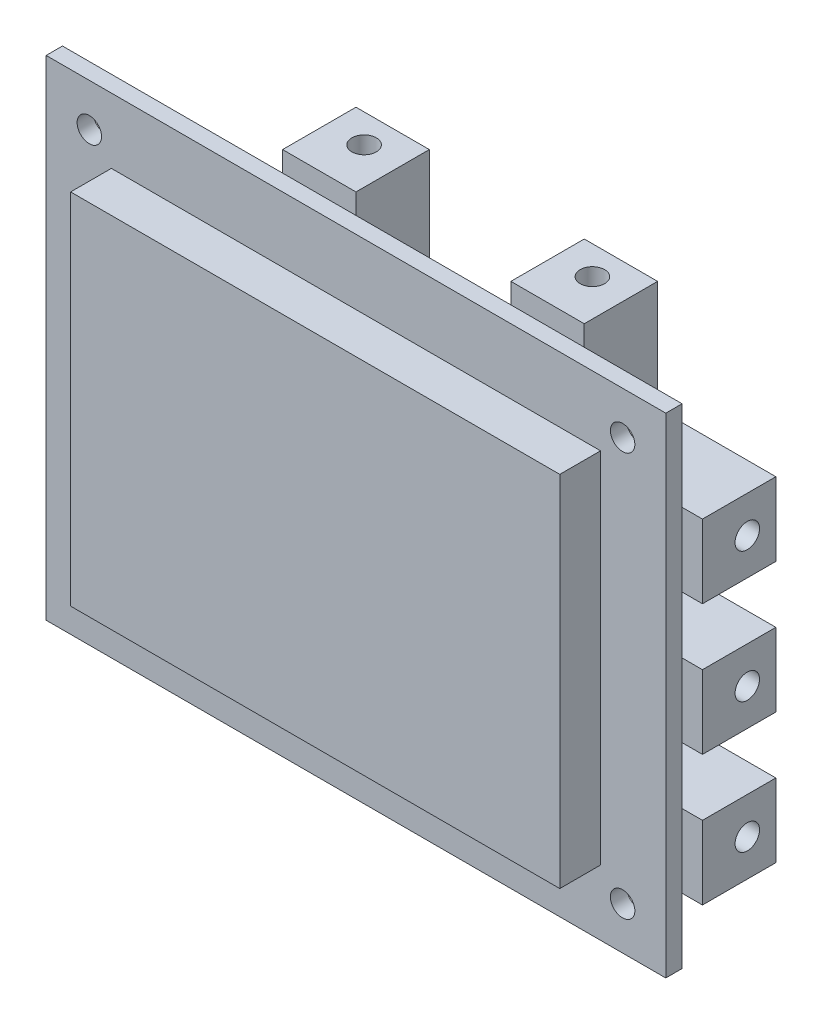
SolidWorks part; units mm, degrees
ref_plane "前视基准面" through (0, 0, 0) normal (0, 0, 1) x (1, 0, 0)
ref_plane "上视基准面" through (0, 0, 0) normal (0, 1, 0) x (1, 0, 0)
ref_plane "右视基准面" through (0, 0, 0) normal (1, 0, 0) x (0, 0, -1)
sketch "草图1" plane through (0, 0, 0) normal (0, 0, 1) x (1, 0, 0)
  line L1 (-38, -30) -> (38, -30)
  line L2 (-38, -30) -> (-38, 30)
  line L3 (-38, 30) -> (38, 30)
  line L4 (38, -30) -> (38, 30)
  line L5 (-38, -30) -> (38, 30) construction
  line L6 (-38, 30) -> (38, -30) construction
  circle A0 centre (-32.705, 24.765) radius 1.5
  circle A1 centre (32.705, 24.765) radius 1.5
  circle A2 centre (-32.705, -24.765) radius 1.5
  circle A3 centre (32.705, -24.765) radius 1.5
  point P0 (0, 0)
  dimension "D4" = 32.705
  dimension "D5" = 3
  dimension "D6" = 49.53
  dimension "D7" = 24.765
  dimension "D1" = 76
  dimension "D2" = 60
  dimension "D3" = 65.41
extrude "凸台-拉伸1" add sketch "草图1" along normal blind 2
sketch "草图2" plane through (0, 0, 2) normal (0, 0, 1) x (1, 0, 0)
  line L0 (38, 30) -> (-38, 30) construction
  line L1 (-30, -22) -> (30, -22)
  line L2 (-30, -22) -> (-30, 22)
  line L3 (-30, 22) -> (30, 22)
  line L4 (30, -22) -> (30, 22)
  line L5 (-30, -22) -> (30, 22) construction
  line L6 (-30, 22) -> (30, -22) construction
  line L7 (38, -30) -> (38, 30) construction
  point P0 (0, 0)
  dimension "D1" = 8
  dimension "D2" = 8
extrude "凸台-拉伸2" add sketch "草图2" along normal blind 5
sketch "草图3" plane through (0, 0, 0) normal (0, 0, -1) x (-1, 0, 0)
  line L0 (38, -30) -> (-38, -30) construction
  line L1 (-40.5, -13) -> (-28.5, -13)
  line L2 (-40.5, -13) -> (-40.5, -22)
  line L3 (-40.5, -22) -> (-28.5, -22)
  line L4 (-28.5, -13) -> (-28.5, -22)
  line L13 (-38, -30) -> (-38, 30) construction
  line L14 (-40.5, 3) -> (-40.5, -6)
  line L15 (-40.5, 3) -> (-28.5, 3)
  line L16 (-28.5, 3) -> (-28.5, -6)
  line L17 (-40.5, -6) -> (-28.5, -6)
  line L18 (-40.5, 19) -> (-40.5, 10)
  line L19 (-40.5, 19) -> (-28.5, 19)
  line L20 (-28.5, 19) -> (-28.5, 10)
  line L21 (-40.5, 10) -> (-28.5, 10)
  line L22 (-38, 30) -> (38, 30) construction
  line L23 (-26, 20.5) -> (-17, 20.5)
  line L24 (-26, 20.5) -> (-26, 32.5)
  line L25 (-26, 32.5) -> (-17, 32.5)
  line L26 (-17, 20.5) -> (-17, 32.5)
  line L27 (2, 20.5) -> (11, 20.5)
  line L28 (2, 20.5) -> (2, 32.5)
  line L29 (2, 32.5) -> (11, 32.5)
  line L30 (11, 20.5) -> (11, 32.5)
  line L31 (38, 30) -> (38, -30) construction
  line L32 (-6, -30) -> (29, -30)
  line L33 (-6, -30) -> (-6, -25)
  line L34 (-6, -25) -> (29, -25)
  line L35 (29, -30) -> (29, -25)
  line L37 (38, -22.5) -> (33, -22.5)
  line L38 (38, -22.5) -> (38, -12.5)
  line L39 (38, -12.5) -> (33, -12.5)
  line L40 (33, -22.5) -> (33, -12.5)
  dimension "D1" = 8
  dimension "D2" = 9
  dimension "D3" = 12
  dimension "D4" = 2.5
  dimension "D5" = 3
  dimension "D6" = 12
  dimension "D7" = 9
  dimension "D8" = 12
  dimension "D9" = 2.5
  dimension "D10" = 19
  dimension "D11" = 9
  dimension "D12" = 12
  dimension "D13" = 2.5
  dimension "D14" = 9
  dimension "D15" = 5
  dimension "D16" = 35
  dimension "D17" = 7.5
  dimension "D18" = 5
  dimension "D19" = 10
extrude "凸台-拉伸3" add sketch "草图3" along normal blind 9
sketch "草图4" plane through (40.5, 0, 0) normal (1, 0, 0) x (0, 0, -1)
  line L0 (9, -13) -> (9, -22) construction
  line L1 (9, -22) -> (0, -22) construction
  circle A0 centre (5.5, -17.5) radius 1.5
  circle A1 centre (5.5, -1.5) radius 1.5
  circle A2 centre (5.5, 14.5) radius 1.5
  dimension "D2" = 3
  dimension "D3" = 4.5
  dimension "D1" = 3.5
  dimension "D4" = 3
extrude "切除-拉伸1" cut sketch "草图4" against normal blind 26
sketch "草图5" plane through (0, 32.5, 0) normal (0, 1, 0) x (1, 0, 0)
  line L0 (-11, 9) -> (-2, 9) construction
  line L1 (-2, 9) -> (-2, 0) construction
  line L2 (17, 9) -> (17, 0) construction
  line L3 (17, 9) -> (26, 9) construction
  circle A0 centre (21.5, 5.5) radius 1.5
  circle A1 centre (-6.5, 5.5) radius 1.5
  dimension "D2" = 3
  dimension "D3" = 4.5
  dimension "D6" = 3
  dimension "D1" = 3.5
  dimension "D4" = 4.5
  dimension "D5" = 3.5
extrude "切除-拉伸2" cut sketch "草图5" against normal blind 26
